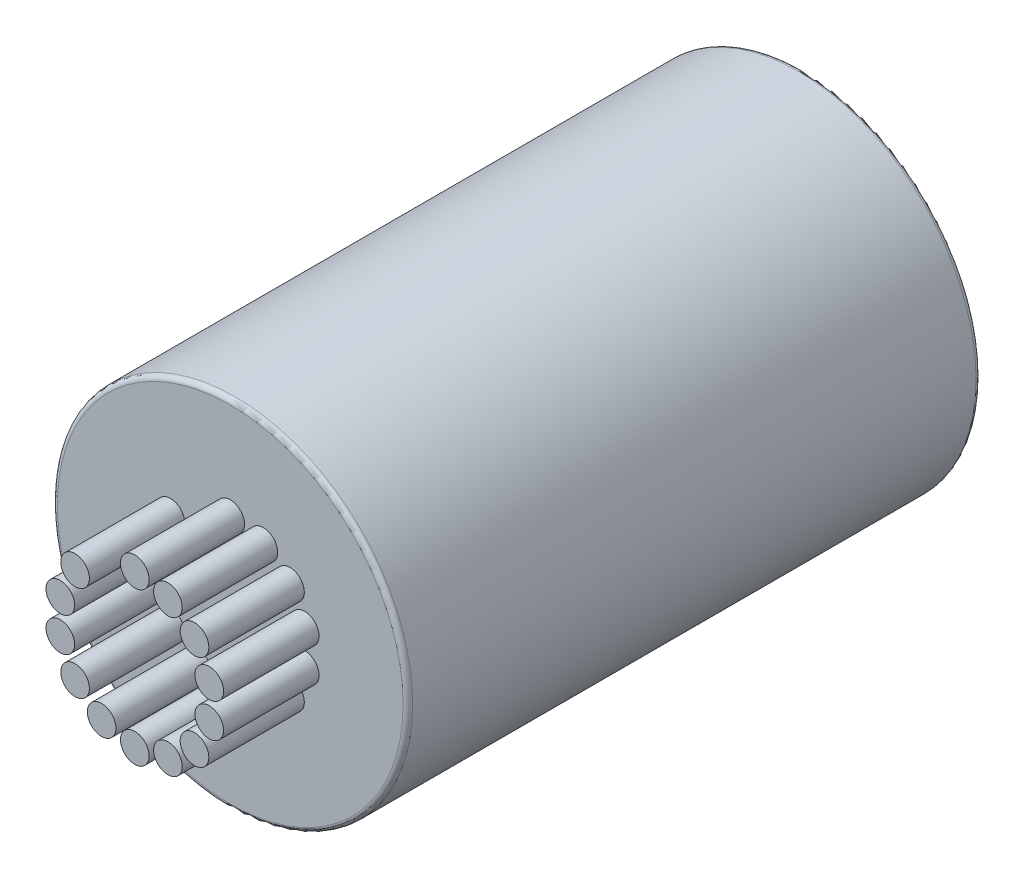
SolidWorks part; units mm, degrees
ref_plane "Front Plane" through (0, 0, 0) normal (0, 0, 1) x (1, 0, 0)
ref_plane "Top Plane" through (0, 0, 0) normal (0, 1, 0) x (1, 0, 0)
ref_plane "Right Plane" through (0, 0, 0) normal (1, 0, 0) x (0, 0, -1)
sketch "Sketch1" plane through (0, 0, 0) normal (0, 0, 1) x (1, 0, 0)
  circle A0 centre (0, 0) radius 9.3
  dimension "D1" = 18.6
extrude "Boss-Extrude1" add sketch "Sketch1" along normal blind 30
sketch "Sketch2" plane through (0, 0, 0) normal (0, 0, -1) x (-1, 0, 0)
  circle A0 centre (0, 0) radius 7.5
  dimension "D1" = 15
extrude "Cut-Extrude1" cut sketch "Sketch2" against normal blind 0.1
sketch "Sketch3" plane through (0, 0, 30) normal (0, 0, 1) x (1, 0, 0)
  circle A13 centre (0, 4) radius 0.75
  circle A14 centre (1.7355, 3.6039) radius 0.75
  circle A15 centre (3.1273, 2.494) radius 0.75
  circle A16 centre (3.8997, 0.8901) radius 0.75
  circle A17 centre (3.8997, -0.8901) radius 0.75
  circle A18 centre (3.1273, -2.494) radius 0.75
  circle A19 centre (1.7355, -3.6039) radius 0.75
  circle A20 centre (0, -4) radius 0.75
  circle A21 centre (-1.7355, -3.6039) radius 0.75
  circle A22 centre (-3.1273, -2.494) radius 0.75
  circle A23 centre (-3.8997, -0.8901) radius 0.75
  circle A49 centre (-3.8997, 0.8901) radius 0.75
  circle A50 centre (-3.1273, 2.494) radius 0.75
  circle A52 centre (-1.7355, 3.6039) radius 0.75 [skipped]
  point P30 (0, 0)
  point P54 (0, 0)
  dimension "D3" = 14
  dimension "D2" = 1.5
  dimension "D1" = 4
extrude "Boss-Extrude2" add sketch "Sketch3" along normal blind 5
fillet "Fillet1" radius 0.25 2 edges at (9.3, 0, 30) (9.3, 0, 0)
